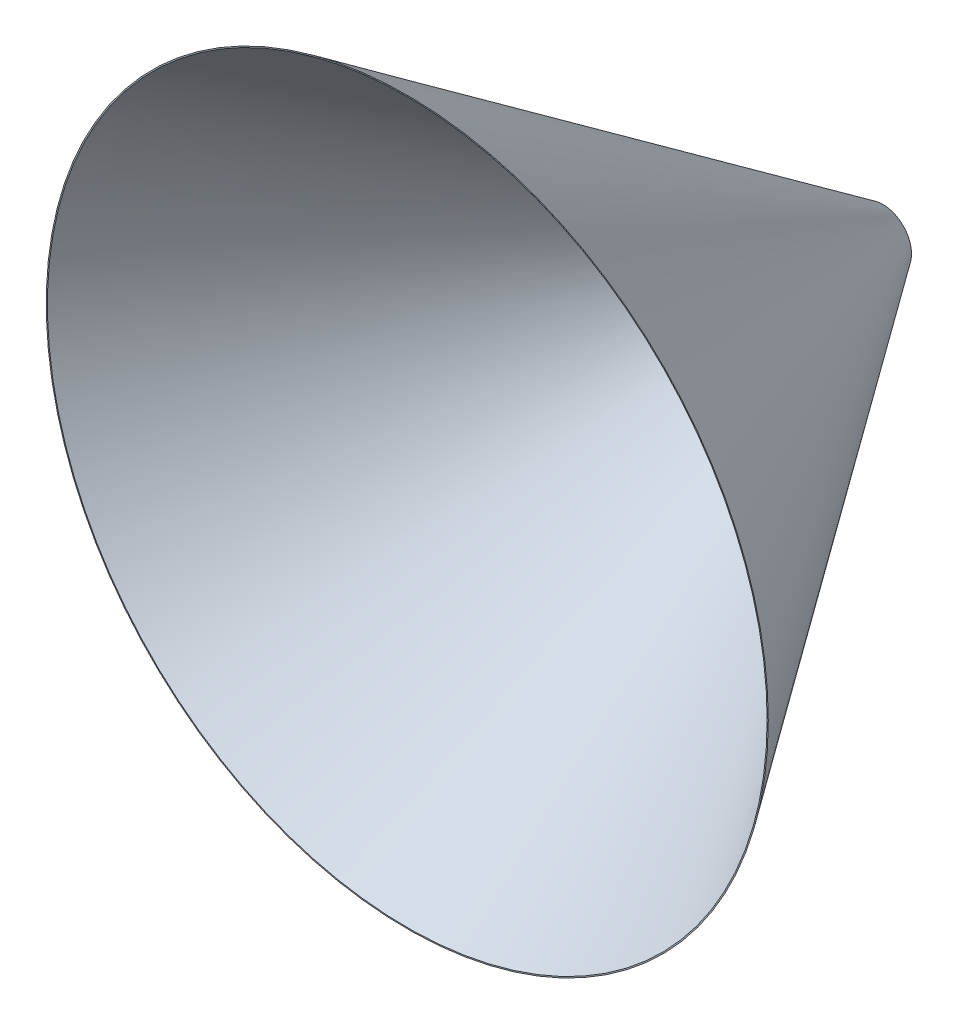
SolidWorks part; units mm, degrees
ref_plane "前视基准面" through (0, 0, 0) normal (0, 0, 1) x (1, 0, 0)
ref_plane "上视基准面" through (0, 0, 0) normal (0, 1, 0) x (1, 0, 0)
ref_plane "右视基准面" through (0, 0, 0) normal (1, 0, 0) x (0, 0, -1)
sketch "草图1" plane through (0, 0, 0) normal (0, 0, 1) x (1, 0, 0)
  circle A0 centre (0, 0) radius 3
  dimension "D1" = 6
extrude "凸台-拉伸1" add sketch "草图1" along normal blind 50 draft 34.95 draft outward yes
shell "抽壳1" thickness 0.1
